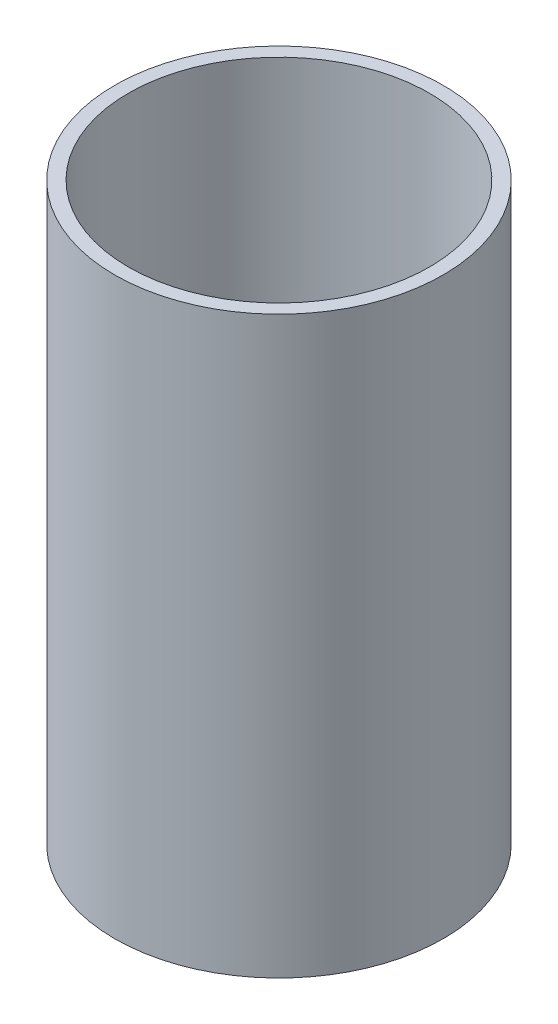
SolidWorks part; units mm, degrees
ref_plane "Front Plane" through (0, 0, 0) normal (0, 0, 1) x (1, 0, 0)
ref_plane "Top Plane" through (0, 0, 0) normal (0, 1, 0) x (1, 0, 0)
ref_plane "Right Plane" through (0, 0, 0) normal (1, 0, 0) x (0, 0, -1)
sketch "Sketch1" plane through (0, 0, 0) normal (0, 1, 0) x (1, 0, 0)
  circle A0 centre (0, 0) radius 12
  circle A1 centre (0, 0) radius 11
  dimension "D1" = 24
  dimension "D2" = 22
extrude "Boss-Extrude1" add sketch "Sketch1" against normal blind 42
